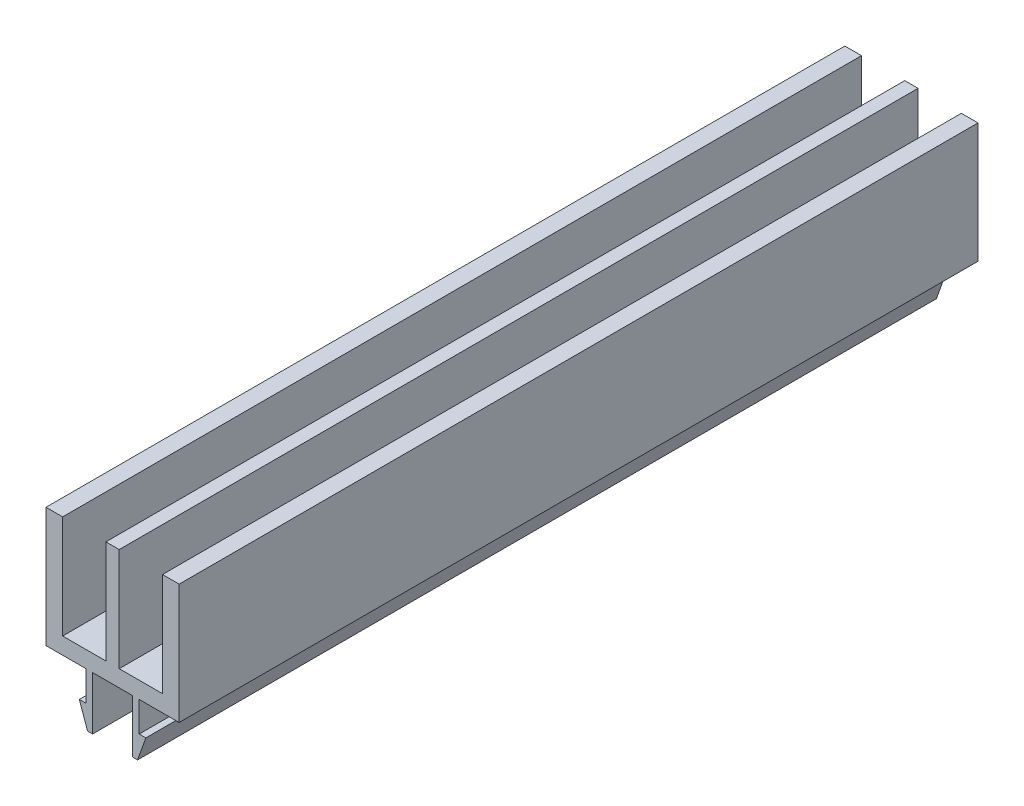
SolidWorks part; units mm, degrees
ref_plane "Plan de face" through (0, 0, 0) normal (0, 0, 1) x (1, 0, 0)
ref_plane "Plan de dessus" through (0, 0, 0) normal (0, 1, 0) x (1, 0, 0)
ref_plane "Plan de droite" through (0, 0, 0) normal (1, 0, 0) x (0, 0, -1)
ref_plane "Plan1" through (0, 0, 50) normal (0, 0, 1) x (1, 0, 0)
sketch "Esquisse1" plane through (0, 0, 50) normal (0, 0, 1) x (1, 0, 0)
  line L0 (-1, 2.5) -> (-7.5, 2.5)
  line L1 (-7.5, 2.5) -> (-7.5, 18)
  line L2 (-7.5, 18) -> (-10, 18)
  line L3 (-10, 18) -> (-10, 0)
  line L4 (-10, 0) -> (-4, 0)
  line L5 (-4, 0) -> (-4, -4.5)
  line L6 (-4, -4.5) -> (-5, -4.5)
  line L7 (-5, -4.5) -> (-3.75, -8)
  line L8 (-3.75, -8) -> (-3, -8)
  line L9 (-3, -8) -> (-3, 0)
  line L10 (-3, 0) -> (3, 0)
  line L11 (3, 0) -> (3, -8)
  line L12 (3, -8) -> (3.75, -8)
  line L13 (3.75, -8) -> (5, -4.5)
  line L14 (5, -4.5) -> (4, -4.5)
  line L15 (4, -4.5) -> (4, 0)
  line L16 (4, 0) -> (10, 0)
  line L17 (10, 0) -> (10, 18)
  line L18 (10, 18) -> (7.5, 18)
  line L19 (7.5, 18) -> (7.5, 2.5)
  line L20 (7.5, 2.5) -> (1, 2.5)
  line L21 (1, 2.5) -> (1, 18)
  line L22 (1, 18) -> (-1, 18)
  line L23 (-1, 18) -> (-1, 2.5)
extrude "Boss.-Extru.1" add sketch "Esquisse1" against normal blind 120
